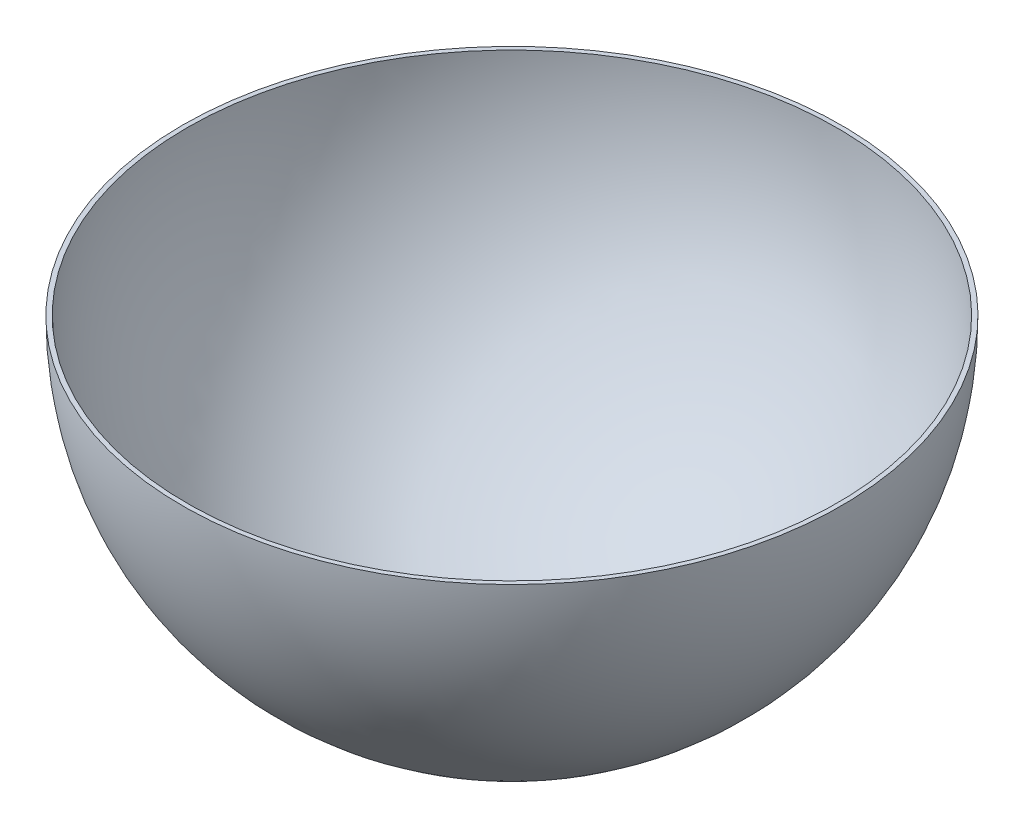
SolidWorks part; units mm, degrees
ref_plane "Front Plane" through (0, 0, 0) normal (0, 0, 1) x (1, 0, 0)
ref_plane "Top Plane" through (0, 0, 0) normal (0, 1, 0) x (1, 0, 0)
ref_plane "Right Plane" through (0, 0, 0) normal (1, 0, 0) x (0, 0, -1)
sketch "Sketch1" plane through (0, 0, 0) normal (0, 0, 1) x (1, 0, 0)
  line L0 (0, 0) -> (0, -294.386) construction
  line L1 (-294.386, 0) -> (-298.45, 0)
  line L2 (0, -294.386) -> (0, -298.45)
  circle A0 centre (0, 0) radius 298.45
  circle A1 centre (0, 0) radius 294.386
  dimension "D1" = 596.9
  dimension "D2" = 588.772
revolve "Revolve1" add sketch "Sketch1" angle 360 about L0
sketch "Sketch2" plane through (-309.812, -388.2515, -376.8657) normal (0, 1, 0) x (1, 0, 0)
  circle A0 centre (309.812, -376.8657) radius 1.143 construction
  circle A1 centre (309.812, -376.8657) radius 1.143
extrude "Cut-Extrude1" cut sketch "Sketch2" along normal blind 1203.198
